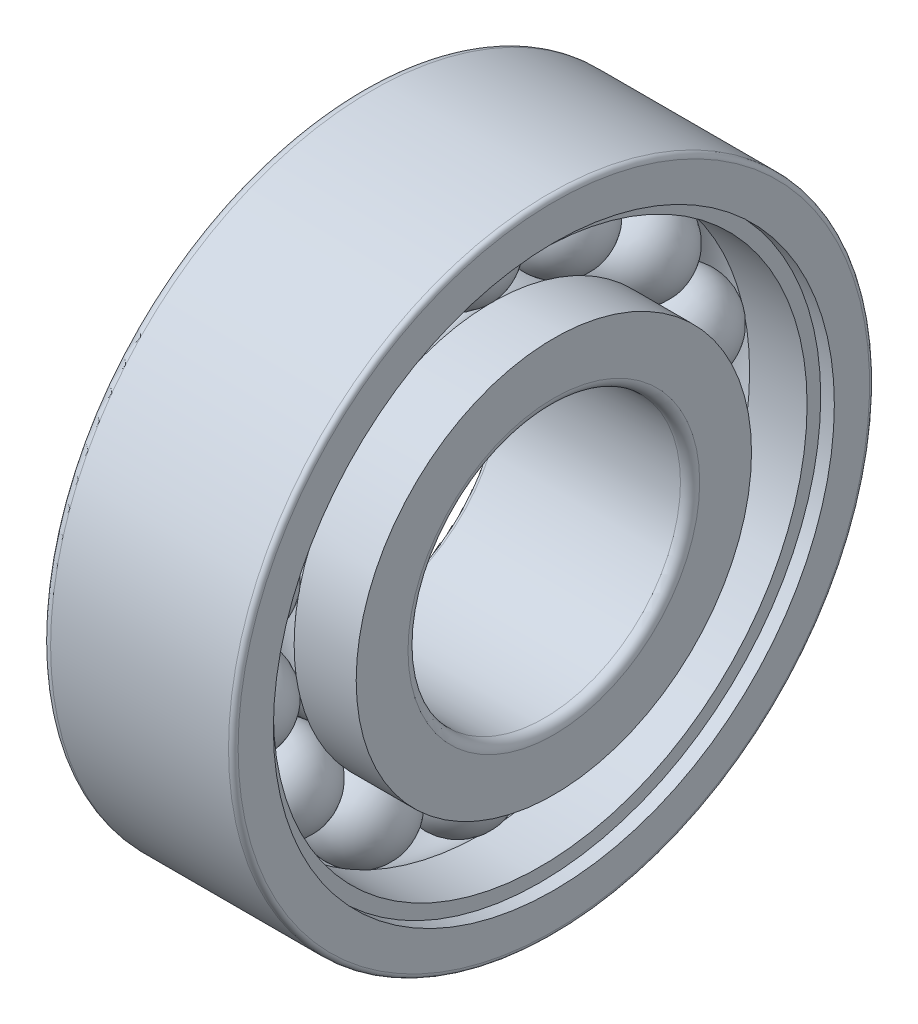
SolidWorks part; units mm, degrees
ref_plane "Front" through (0, 0, 0) normal (0, 0, 1) x (1, 0, 0)
ref_plane "Top" through (0, 0, 0) normal (0, 1, 0) x (1, 0, 0)
ref_plane "Right" through (0, 0, 0) normal (1, 0, 0) x (0, 0, -1)
sketch "Sketch1" plane through (0, 0, 0) normal (0, 0, 1) x (1, 0, 0)
  line L0 (-3.0919, 0) -> (2.899, 0) construction
  line L1 (-3.0919, 14.25) -> (2.899, 14.25) construction
  line L2 (-2.875, 14.25) -> (2.875, 14.25)
  arc A0 (-2.875, 14.25) -> (2.875, 14.25) centre (0, 14.25) ccw
  dimension "R" = 2.875
  dimension "D1" = 14.25
revolve "Revolve1" add sketch "Sketch1" angle 360 about L1
sketch "Sketch2" plane through (0, 0, 0) normal (0, 0, 1) x (1, 0, 0)
  line L0 (-6, 12.3333) -> (-2.1295, 12.3333)
  line L1 (6, 12.3333) -> (6, 8.5)
  line L2 (6, 8.5) -> (-6, 8.5)
  line L3 (-6, 8.5) -> (-6, 12.3333)
  line L4 (-2.9924, 0) -> (3.9982, 0) construction
  line L5 (-1.8743, 14.25) -> (3.1755, 14.25) construction
  line L7 (2.1295, 12.3333) -> (6, 12.3333)
  line L8 (-6, 6.2861) -> (-6, 1.454) construction
  arc A0 (-2.1295, 12.3333) -> (2.1295, 12.3333) centre (0, 14.25) ccw
  dimension "D1" = 14.25
  dimension "B" = 12
  dimension "D2" = 2.865
  dimension "d" = 17
  dimension "D3" = 24.6667
  dimension "T" = 12
  dimension "D6" = 6
revolve "Revolve2" add sketch "Sketch2" angle 360 about L4
sketch "Sketch3" plane through (0, 0, 0) normal (0, 0, 1) x (1, 0, 0)
  line L0 (-6, 16.1667) -> (-6, 20)
  line L1 (-6, 20) -> (6, 20)
  line L2 (6, 20) -> (6, 17.5017)
  line L3 (5.15, 16.6517) -> (1.5621, 16.6517)
  line L4 (-2.9924, 0) -> (3.4329, 0) construction
  line L6 (-1.7375, 14.25) -> (2.2712, 14.25) construction
  line L7 (-2.1295, 16.1667) -> (-6, 16.1667)
  line L8 (5.15, 16.6517) -> (5.15, 17.5017)
  line L9 (5.15, 17.5017) -> (6, 17.5017)
  arc A0 (1.5621, 16.6517) -> (-2.1295, 16.1667) centre (0, 14.25) ccw
  dimension "D1" = 14.25
  dimension "D4" = 2.865
  dimension "B" = 12
  dimension "DD" = 40
  dimension "D3" = 33.3033
  dimension "D5" = 32.3333
  dimension "D6" = 0.85
  dimension "D7" = 0.85
  dimension "D2" = 6
revolve "Revolve3" add sketch "Sketch3" angle 360 about L4
pattern_circular "Circular-Pattern1" count 14 over 360 about axis through (0, 0, 0) along (1, 0, 0) of "Revolve1"
fillet "Fillet1" radius 0.6 2 edges at (6, 0, 8.5) (-6, 0, 20)
fillet "Fillet2" radius 0.3 2 edges at (6, 0, 20) (-6, 0, 8.5)
equation "\"R@Sketch1\" =  ( \"DD@Sketch3\" - \"d@Sketch2\" )  / 8"
equation "\"D1@Sketch1\"=(\"d@Sketch2\"+\"DD@Sketch3\")/4"
equation "\"D1@Sketch2\"=(\"d@Sketch2\"+\"DD@Sketch3\")/4"
equation "\"D3@Sketch2\" =  \"d@Sketch2\"+  ( \"DD@Sketch3\" - \"d@Sketch2\" )  /3"
equation "\"D2@Sketch2\" =  ( \"DD@Sketch3\" - \"d@Sketch2\" )  / 8 - 0.01"
equation "\"D6@Sketch2\" = \"B@Sketch2\" / 2"
equation "\"B@Sketch3\" = \"B@Sketch2\""
equation "\"D2@Sketch3\" = \"B@Sketch3\" / 2"
equation "\"D1@Sketch3\"=(\"d@Sketch2\"+\"DD@Sketch3\")/4"
equation "\"D3@Sketch3\" = (  \"DD@Sketch3\" -  (\"DD@Sketch3\" - \"d@Sketch2\"  )  / 3 )  * 1.03"
equation "\"D5@Sketch3\" = \"DD@Sketch3\" -  (  \"DD@Sketch3\" - \"d@Sketch2\")  / 3"
equation "\"D6@Sketch3\" = \"d@Sketch2\" / 20"
equation "\"D7@Sketch3\"=\"D6@Sketch3\""
equation "\"D4@Sketch3\"=(\"DD@Sketch3\"-\"d@Sketch2\")/8-0.01"
equation "\"m@Circular-Pattern1\" = int( 3.14159265 / atn(\"R@Sketch1\" / sqr((\"d@Sketch2\"+\"DD@Sketch3\")/4 * (\"d@Sketch2\"+\"DD@Sketch3\")/4 - \"R@Sketch1\" *  \"R@Sketch1\")))-1"
